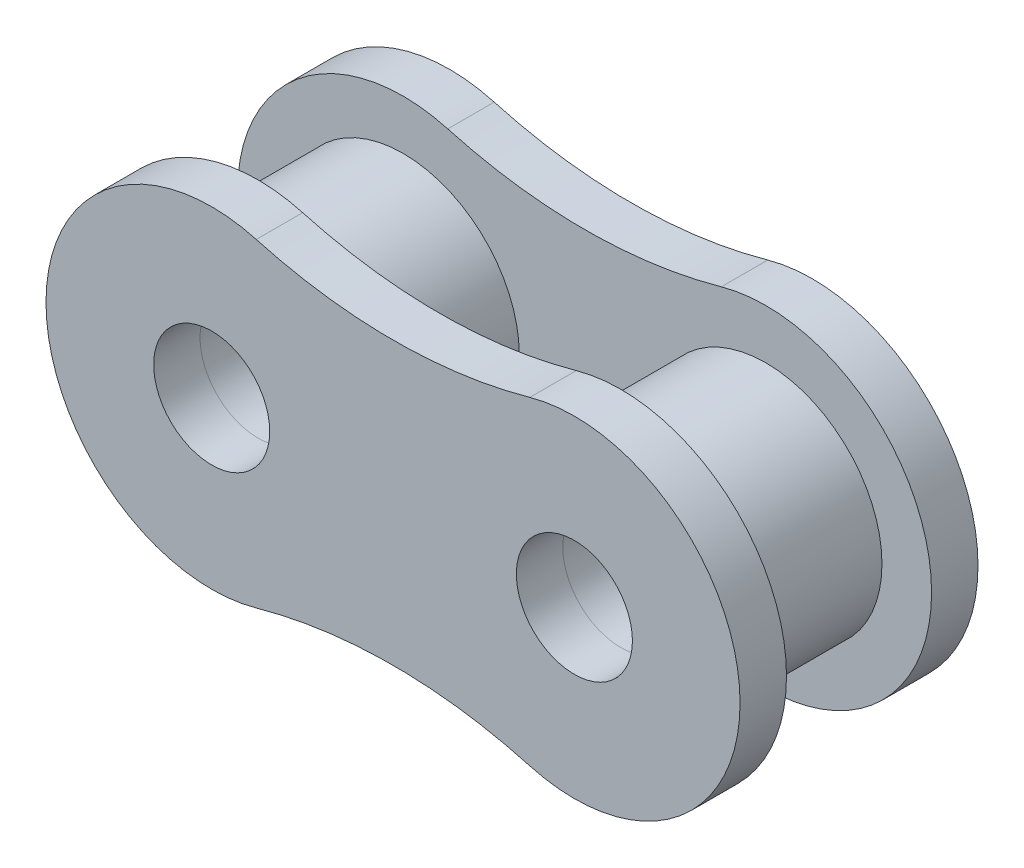
SolidWorks part; units mm, degrees
ref_plane "Front Plane" through (0, 0, 0) normal (0, 0, 1) x (1, 0, 0)
ref_plane "Top Plane" through (0, 0, 0) normal (0, 1, 0) x (1, 0, 0)
ref_plane "Right Plane" through (0, 0, 0) normal (1, 0, 0) x (0, 0, -1)
sketch "Sketch1" plane through (0, 0, 0) normal (0, 0, 1) x (1, 0, 0)
  line L0 (-7.9375, 0) -> (7.9375, 0) construction
  line L1 (-7.9375, 7.2517) -> (-7.9375, -7.2517) construction
  line L2 (0, -6.1639) -> (0, 6.1639) construction
  circle A0 centre (-7.9375, 0) radius 5.08
  circle A1 centre (7.9375, 0) radius 5.08
  circle A2 centre (-7.9375, 0) radius 2.54
  circle A3 centre (7.9375, 0) radius 2.54
  arc A4 (-5.9866, 6.9843) -> (-5.9866, -6.9843) centre (-7.9375, 0) ccw
  arc A5 (5.9866, -6.9843) -> (5.9866, 6.9843) centre (7.9375, 0) ccw
  arc A6 (-5.9866, 6.9843) -> (5.9866, 6.9843) centre (0, 28.4166) ccw
  arc A7 (-5.9866, -6.9843) -> (5.9866, -6.9843) centre (0, -28.4166) cw
  dimension "Roller Dia" = 10.16
  dimension "Pin Dia" = 5.08
  dimension "Pitch" = 15.875
  dimension "H" = 14.5034
  dimension "D2" = 12.3279
sketch "Sketch2" plane through (0, 0, 0) normal (0, 1, 0) x (1, 0, 0)
  line L0 (0, 3.175) -> (0, -3.175) construction
  point P2 (0, -5.207)
  point P4 (0, 5.207)
  point P5 (0, 5.2578)
  point P6 (0, 7.2898)
  dimension "W" = 6.35
  dimension "T" = 2.032
  dimension "D1" = 2.032
  dimension "D2" = 2.032
  dimension "D3" = 0.0508
ref_plane "Plane1" through (0, 0, 3.175) normal (0, 0, 1) x (1, 0, 0)
ref_plane "Plane2" through (0, 0, -5.2578) normal (0, 0, 1) x (1, 0, 0)
sketch "Sketch4" plane through (0, 0, 0) normal (0, 0, 1) x (1, 0, 0)
  circle A0 centre (-7.9375, 0) radius 5.08 construction
  circle A1 centre (-7.9375, 0) radius 5.08
  circle A2 centre (7.9375, 0) radius 5.08 construction
  circle A3 centre (7.9375, 0) radius 5.08
  circle A4 centre (-7.9375, 0) radius 2.5654
  circle A5 centre (7.9375, 0) radius 2.5654
  dimension "D1" = 5.1308
  dimension "D2" = 5.1308
extrude "Boss-Extrude1" add sketch "Sketch4" along normal mid plane 6.35
sketch "Sketch5" plane through (0, 0, 3.175) normal (0, 0, 1) x (1, 0, 0)
  arc A0 (-5.9866, 6.9843) -> (-5.9866, -6.9843) centre (-7.9375, 0) ccw construction
  arc A1 (-5.9866, 6.9843) -> (5.9866, 6.9843) centre (0, 28.4166) ccw construction
  circle A2 centre (-7.9375, 0) radius 2.54 construction
  arc A3 (5.9866, -6.9843) -> (5.9866, 6.9843) centre (7.9375, 0) ccw construction
  circle A4 centre (7.9375, 0) radius 2.54 construction
  arc A5 (5.9866, -6.9843) -> (-5.9866, -6.9843) centre (0, -28.4166) ccw construction
  arc A6 (-5.9866, 6.9843) -> (-5.9866, -6.9843) centre (-7.9375, 0) ccw
  arc A7 (-5.9866, 6.9843) -> (5.9866, 6.9843) centre (0, 28.4166) ccw
  circle A8 centre (-7.9375, 0) radius 2.54
  arc A9 (5.9866, -6.9843) -> (5.9866, 6.9843) centre (7.9375, 0) ccw
  circle A10 centre (7.9375, 0) radius 2.54
  arc A11 (5.9866, -6.9843) -> (-5.9866, -6.9843) centre (0, -28.4166) ccw
extrude "Boss-Extrude2" add sketch "Sketch5" along normal up to vertex (2.032 mm away) separate body up to point (0, 0, 5.207)
pattern_linear "LPattern1" count 2 spacing 15.875 along (1, 0, 0) of bodies 102
sketch "Sketch7" plane through (0, 0, -5.2578) normal (0, 0, 1) x (1, 0, 0)
  line L0 (23.8125, 6.3815) -> (23.8125, -6.3815) construction
  arc A0 (9.7065, 6.1314) -> (9.7065, -6.1314) centre (7.9375, 0) ccw
  arc A1 (22.0435, -6.1314) -> (22.0435, 6.1314) centre (23.8125, 0) ccw
  arc A2 (5.9866, -6.9843) -> (5.9866, 6.9843) centre (7.9375, 0) ccw construction
  circle A3 centre (23.8125, 0) radius 5.08 construction
  arc A4 (9.7065, 6.1314) -> (22.0435, 6.1314) centre (15.875, 27.5121) ccw
  arc A5 (9.7065, -6.1314) -> (22.0435, -6.1314) centre (15.875, -27.5121) cw
  arc A6 (-5.9866, 6.9843) -> (5.9866, 6.9843) centre (0, 28.4166) ccw construction
  circle A7 centre (7.9375, 0) radius 2.54 construction
  circle A8 centre (7.9375, 0) radius 2.54
  circle A9 centre (23.8125, 0) radius 2.54
  dimension "D2" = 12.763
extrude "Boss-Extrude3" add sketch "Sketch7" against normal up to vertex (2.032 mm away) separate body up to point (0, 0, -7.2898)
mirror "Mirror1" about plane through (0, 0, 0) normal (0, 0, 1) of bodies 103 105
sketch "Sketch8" plane through (0, 0, 0) normal (0, 0, 1) x (1, 0, 0)
  circle A0 centre (7.9375, 0) radius 2.54
  circle A1 centre (23.8125, 0) radius 2.54
  circle A2 centre (7.9375, 0) radius 2.54 construction
  circle A3 centre (23.8125, 0) radius 2.54 construction
extrude "Boss-Extrude4" add sketch "Sketch8" against normal blind 10.16 and the other way blind 10.16 separate body
delete or keep bodies "Body-Delete1" type delete bodies bodies 104
delete or keep bodies "Body-Delete/Keep 1" type delete bodies bodies 105 109 107 108
equation "\"D2@Sketch1\" =\"H@Sketch1\"*.85"
equation "\"D1@Sketch2\" = \"T@Sketch2\""
equation "\"D1@Sketch4\" = \"Pin Dia@Sketch1\"+.002"
equation "\"D2@Sketch4\" = \"D1@Sketch4\""
equation "\"D1@Boss-Extrude1\" = \"W@Sketch2\""
equation "\"D2@Sketch2\" = \"T@Sketch2\""
equation "\"D3@LPattern1\" = \"Pitch@Sketch1\""
equation "\"D2@Sketch7\" = \"H@Sketch1\"*.88"
